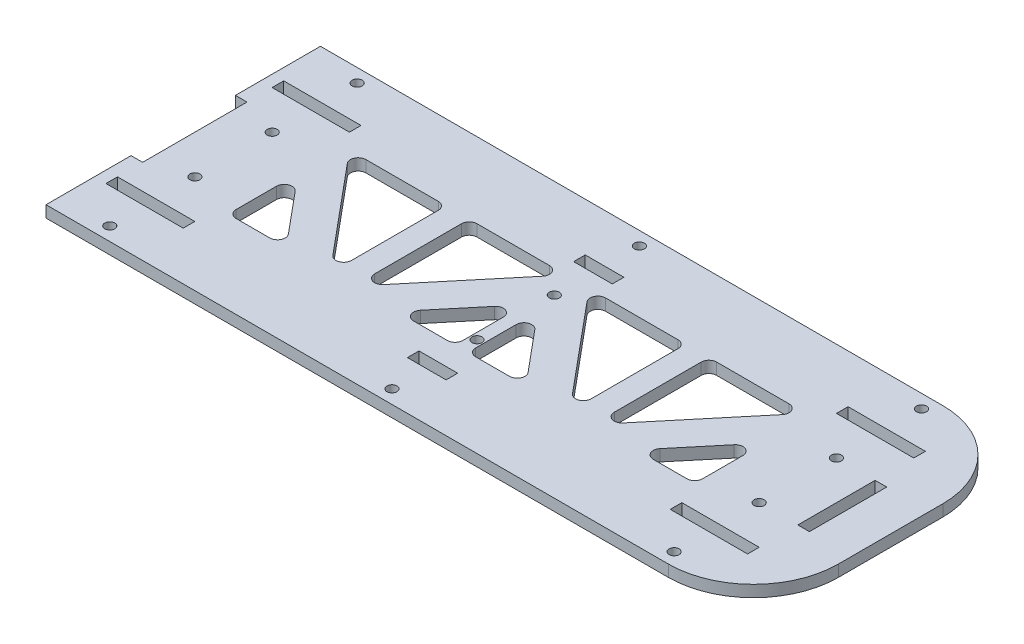
SolidWorks part; units mm, degrees
material "Oak"
ref_plane "Front Plane" through (0, 0, 0) normal (0, 0, 1) x (1, 0, 0)
ref_plane "Top Plane" through (0, 0, 0) normal (0, 1, 0) x (1, 0, 0)
ref_plane "Right Plane" through (0, 0, 0) normal (1, 0, 0) x (0, 0, -1)
sketch "Sketch1" plane through (0, 0, 0) normal (0, 1, 0) x (1, 0, 0)
  line L0 (0, 0) -> (0, 106.5) construction
  line L1 (-150, 106.5) -> (150, 106.5)
  line L2 (-150, 106.5) -> (-150, -106.5)
  line L3 (-150, -106.5) -> (150, -106.5)
  line L4 (150, 106.5) -> (150, -106.5)
  line L5 (0, 0) -> (150, 0) construction
  dimension "D1" = 300
  dimension "D2" = 213
extrude "Boss-Extrude1" add sketch "Sketch1" along normal blind 3
sketch "Sketch2" plane through (0, 3, 0) normal (0, 1, 0) x (1, 0, 0)
  line L0 (-150, 106.5) -> (-150, -106.5) construction
  line L1 (150, 106.5) -> (-150, 106.5) construction
  line L2 (-150, 85.5) -> (-147, 85.5)
  line L3 (-150, 85.5) -> (-150, 106.5)
  line L4 (-150, 106.5) -> (-147, 106.5)
  line L6 (-147, 85.5) -> (-147, 106.5)
  line L7 (-150, -13.5) -> (-150, 0)
  line L8 (-150, 64.5) -> (-147, 64.5)
  line L9 (-150, 64.5) -> (-150, 43.5)
  line L10 (0, 0) -> (-147, 0) construction
  line L11 (-150, 43.5) -> (-147, 43.5)
  line L12 (-147, 64.5) -> (-147, 43.5)
  line L13 (-150, 13.5) -> (-147, 13.5)
  line L14 (-150, 13.5) -> (-150, 0)
  line L16 (-147, 13.5) -> (-147, -13.5)
  line L17 (-150, -13.5) -> (-147, -13.5)
  line L18 (-147, -64.5) -> (-147, -43.5)
  line L19 (-150, -43.5) -> (-147, -43.5)
  line L20 (-150, -64.5) -> (-150, -43.5)
  line L21 (-150, -64.5) -> (-147, -64.5)
  line L22 (-147, -85.5) -> (-147, -106.5)
  line L23 (-150, -106.5) -> (-147, -106.5)
  line L24 (-150, -85.5) -> (-150, -106.5)
  line L25 (-150, -85.5) -> (-147, -85.5)
  dimension "D1" = 21
  dimension "D2" = 21
  dimension "D3" = 30
  dimension "D4" = 3
  dimension "D5" = 21
extrude "Cut-Extrude1" cut sketch "Sketch2" against normal through all
sketch "Sketch3" plane through (0, 3, 0) normal (0, 1, 0) x (1, 0, 0)
  line L0 (0, 0) -> (-147, 0) construction
  line L1 (-147, 23) -> (-127, 23)
  line L2 (-147, 23) -> (-147, 20)
  line L3 (-147, 20) -> (-127, 20)
  line L4 (-127, 23) -> (-127, 20)
  line L5 (-69, 23) -> (-59, 23)
  line L6 (-69, 23) -> (-69, 20)
  line L7 (-69, 20) -> (-59, 20)
  line L8 (-59, 23) -> (-59, 20)
  line L9 (-1, 23) -> (19, 23)
  line L10 (-1, 23) -> (-1, 20)
  line L11 (-1, 20) -> (19, 20)
  line L12 (19, 23) -> (19, 20)
  line L13 (-147, -13.5) -> (-147, 13.5) construction
  line L14 (19, -23) -> (19, -20)
  line L15 (-1, -20) -> (19, -20)
  line L16 (-1, -23) -> (-1, -20)
  line L17 (-1, -23) -> (19, -23)
  line L18 (-59, -23) -> (-59, -20)
  line L19 (-69, -20) -> (-59, -20)
  line L20 (-69, -23) -> (-69, -20)
  line L21 (-69, -23) -> (-59, -23)
  line L22 (-127, -23) -> (-127, -20)
  line L23 (-147, -20) -> (-127, -20)
  line L24 (-147, -23) -> (-147, -20)
  line L25 (-147, -23) -> (-127, -23)
  dimension "D1" = 20
  dimension "D2" = 20
extrude "Cut-Extrude2" cut sketch "Sketch3" against normal through all
sketch "Sketch4" plane through (0, 3, 0) normal (0, 1, 0) x (1, 0, 0)
  line L1 (19, 10) -> (22, 10)
  line L2 (19, 10) -> (19, -10)
  line L3 (19, -10) -> (22, -10)
  line L4 (22, 10) -> (22, -10)
extrude "Cut-Extrude3" cut sketch "Sketch4" against normal through all
sketch "Sketch6" plane through (0, 3, 0) normal (0, 1, 0) x (1, 0, 0)
  circle A0 centre (-137, 32) radius 1.3
  circle A1 centre (-64, 32) radius 1.3
  circle A4 centre (9, 32) radius 1.3
  circle A6 centre (9, -32) radius 1.3
  circle A8 centre (-64, -32) radius 1.3
  circle A10 centre (-137, -32) radius 1.3
  dimension "D1" = 2.6
extrude "Cut-Extrude4" cut sketch "Sketch6" against normal through all
sketch "Sketch7" plane through (0, 3, 0) normal (0, 1, 0) x (1, 0, 0)
  line L0 (-115, 90) -> (-115, 60)
  line L1 (-115, 60) -> (-85, 60)
  line L2 (-85, 60) -> (-115, 90)
  line L3 (-108, 90) -> (-78, 60)
  line L4 (-78, 60) -> (-78, 90)
  line L5 (-78, 90) -> (-108, 90)
  line L6 (-150, 75) -> (150, 75) construction
  line L7 (-150, 85.5) -> (-150, 64.5) construction
  line L8 (150, -106.5) -> (150, 106.5) construction
  line L9 (-115, 75) -> (-78, 75) construction
  line L10 (-71, 106.5) -> (-71, -106.5) construction
  line L11 (150, 106.5) -> (-147, 106.5) construction
  line L12 (-147, -106.5) -> (150, -106.5) construction
  line L13 (-64, 90) -> (-34, 90)
  line L14 (-64, 60) -> (-64, 90)
  line L15 (-34, 90) -> (-64, 60)
  line L16 (-27, 60) -> (-57, 60)
  line L17 (-57, 60) -> (-27, 90)
  line L18 (-27, 90) -> (-27, 60)
  line L19 (-15, 90) -> (-15, 60)
  line L20 (-15, 60) -> (15, 60)
  line L21 (15, 60) -> (-15, 90)
  line L22 (-8, 90) -> (22, 60)
  line L23 (22, 60) -> (22, 90)
  line L24 (22, 90) -> (-8, 90)
  line L25 (36, 90) -> (66, 90)
  line L26 (36, 60) -> (36, 90)
  line L27 (66, 90) -> (36, 60)
  line L28 (73, 60) -> (43, 60)
  line L29 (43, 60) -> (73, 90)
  line L30 (73, 90) -> (73, 60)
  line L31 (-15, 75) -> (22, 75) construction
  line L32 (85, 90) -> (85, 60)
  line L33 (85, 60) -> (115, 60)
  line L34 (115, 60) -> (85, 90)
  line L35 (92, 90) -> (122, 60)
  line L36 (122, 60) -> (122, 90)
  line L37 (122, 90) -> (92, 90)
  line L38 (-147, 0) -> (150, 0) construction
  line L39 (-147, -13.5) -> (-147, 13.5) construction
  line L43 (-150, -75) -> (150, -75) construction
  line L44 (85, 75) -> (122, 75) construction
  line L45 (166, 90) -> (136, 60) [skipped]
  line L46 (173, 60) -> (143, 60) [skipped]
  line L47 (143, 60) -> (173, 90) [skipped]
  line L48 (173, 90) -> (173, 60) [skipped]
  line L49 (136, 90) -> (166, 90) [skipped]
  line L50 (136, 60) -> (136, 90) [skipped]
  dimension "D1" = 30
  dimension "D2" = 35
  dimension "D3" = 7
  dimension "D4" = 7
  dimension "D5" = 3
extrude "Cut-Extrude5" cut sketch "Sketch7" against normal through all
fillet "Fillet1" radius 4 30 edges at (92, 1.5, -90) (122, 1.5, -90) (122, 1.5, -60) (115, 1.5, -60) (85, 1.5, -90) (85, 1.5, -60) (73, 1.5, -60) (73, 1.5, -90) (43, 1.5, -60) (36, 1.5, -60) (66, 1.5, -90) (36, 1.5, -90) (-8, 1.5, -90) (22, 1.5, -90) (22, 1.5, -60) (-15, 1.5, -60) (15, 1.5, -60) (-15, 1.5, -90) (-57, 1.5, -60) (-27, 1.5, -60) (-27, 1.5, -90) (-34, 1.5, -90) (-64, 1.5, -90) (-64, 1.5, -60) (-78, 1.5, -60) (-78, 1.5, -90) (-108, 1.5, -90) (-115, 1.5, -60) (-85, 1.5, -60) (-115, 1.5, -90)
mirror "Mirror1" about plane through (0, 0, 0) normal (0, 0, 1) of "Fillet1", "Cut-Extrude5"
sketch "Sketch8" plane through (0, 3, 0) normal (0, 1, 0) x (1, 0, 0)
  line L0 (-147, 0) -> (150, 0) construction
  line L1 (-147, -13.5) -> (-147, 13.5) construction
  line L2 (150, -106.5) -> (150, 106.5) construction
  circle A0 centre (-136.9874, -10) radius 1.3
  circle A2 centre (-64, -10) radius 1.3
  circle A4 centre (9, -10) radius 1.3
  circle A6 centre (-136.9874, 10) radius 1.3
  circle A7 centre (-64, 10) radius 1.3
  circle A8 centre (9, 10) radius 1.3
  ellipse E0 centre (-136.9874, -10) end of major axis (-136.9874, -8.15) minor radius 1.85 construction
  dimension "D1" = 2.6
extrude "Cut-Extrude6" cut sketch "Sketch8" against normal through all
sketch "Sketch9" plane through (0, 3, 0) normal (0, 1, 0) x (1, 0, 0)
  line L0 (-147, 43.5) -> (33, 43.5)
  line L1 (33, 43.5) -> (33, -43.5)
  line L2 (33, -43.5) -> (-147, -43.5)
  line L3 (-147, -13.5) -> (-147, 13.5) construction
  line L4 (-147, 43.5) -> (-187.2501, 43.5)
  line L5 (-187.2501, 43.5) -> (-187.2501, 142.9104)
  line L6 (-187.2501, 142.9104) -> (177.7369, 142.9104)
  line L7 (177.7369, 142.9104) -> (177.7369, -148.5651)
  line L8 (177.7369, -148.5651) -> (-187.2501, -148.5651)
  line L9 (-187.2501, -148.5651) -> (-187.2501, -43.5)
  line L10 (-187.2501, -43.5) -> (-147, -43.5)
  dimension "D1" = 180
extrude "Cut-Extrude7" cut sketch "Sketch9" against normal through all contours L6 L7 L8 L9 L10 L2 L1 L0 L4 L5
sketch "Sketch10" plane through (0, 3, 0) normal (0, 1, 0) x (1, 0, 0)
  line L0 (-123, 16) -> (-98, 16)
  line L1 (-98, 16) -> (-98, -14)
  line L2 (-98, -14) -> (-123, 16)
  line L3 (-92, 16) -> (-92, -14)
  line L4 (-92, -14) -> (-67, 16)
  line L5 (-67, 16) -> (-92, 16)
  line L6 (-64, 33.3) -> (-64, -33.3) construction
  line L7 (-150, 43.5) -> (-150, 13.5) construction
  line L8 (-95, -24.4) -> (-132, 20) construction
  line L9 (-124.3333, 4) -> (-124.3333, -14)
  line L10 (-124.3333, -14) -> (-109.3333, -14)
  line L11 (-109.3333, -14) -> (-124.3333, 4)
  line L12 (-95, -43.5) -> (-95, 43.5) construction
  line L13 (33, -43.5) -> (-150, -43.5) construction
  line L14 (-150, 43.5) -> (33, 43.5) construction
  line L15 (-147, 20) -> (-127, 20) construction
  line L16 (-80.6667, -14) -> (-65.6667, 4)
  line L17 (-65.6667, -14) -> (-80.6667, -14)
  line L18 (-65.6667, 4) -> (-65.6667, -14)
  line L19 (-62.3333, 4) -> (-62.3333, -14)
  line L20 (-62.3333, -14) -> (-47.3333, -14)
  line L21 (-47.3333, -14) -> (-62.3333, 4)
  line L22 (-18.6667, -14) -> (-3.6667, 4)
  line L23 (-3.6667, -14) -> (-18.6667, -14)
  line L24 (-3.6667, 4) -> (-3.6667, -14)
  line L25 (-61, 16) -> (-36, 16)
  line L26 (-36, -14) -> (-61, 16)
  line L27 (-36, 16) -> (-36, -14)
  line L28 (-30, -14) -> (-5, 16)
  line L29 (-30, 16) -> (-30, -14)
  line L30 (-5, 16) -> (-30, 16)
  circle A0 centre (-64, 32) radius 1.3 construction
  circle A1 centre (-64, -32) radius 1.3 construction
  dimension "D1" = 25
  dimension "D2" = 30
  dimension "D3" = 3
  dimension "D4" = 3
  dimension "D5" = 4
  dimension "D6" = 55
  dimension "D7" = 15
  dimension "D8" = 9
extrude "Cut-Extrude8" cut sketch "Sketch10" against normal through all
fillet "Fillet2" radius 2 24 edges at (-18.6667, 1.5, 14) (-3.6667, 1.5, 14) (-3.6667, 1.5, -4) (-30, 1.5, 14) (-5, 1.5, -16) (-30, 1.5, -16) (-61, 1.5, -16) (-36, 1.5, -16) (-36, 1.5, 14) (-62.3333, 1.5, 14) (-47.3333, 1.5, 14) (-62.3333, 1.5, -4) (-65.6667, 1.5, 14) (-65.6667, 1.5, -4) (-80.6667, 1.5, 14) (-92, 1.5, 14) (-67, 1.5, -16) (-92, 1.5, -16) (-124.3333, 1.5, 14) (-109.3333, 1.5, 14) (-124.3333, 1.5, -4) (-123, 1.5, -16) (-98, 1.5, -16) (-98, 1.5, 14)
sketch "Sketch11" plane through (0, 3, 0) normal (0, 1, 0) x (1, 0, 0)
  line L0 (33, 43.5) -> (33, -43.5) construction
  line L1 (-150, 43.5) -> (33, 43.5)
  line L2 (-150, 43.5) -> (-150, 35.5)
  line L3 (-150, 35.5) -> (33, 35.5)
  line L4 (33, 43.5) -> (33, 35.5)
  line L5 (-150, -13.5) -> (-150, -43.5) construction
  line L6 (-150, -35.5) -> (33, -35.5)
  line L7 (-150, -35.5) -> (-150, -43.5)
  line L8 (-150, -43.5) -> (33, -43.5)
  line L9 (33, -35.5) -> (33, -43.5)
  dimension "D1" = 8
  dimension "D2" = 8
extrude "Cut-Extrude9" cut sketch "Sketch11" against normal through all
fillet "Fillet3" radius 22 2 edges at (33, 1.5, 35.5) (33, 1.5, -35.5)
